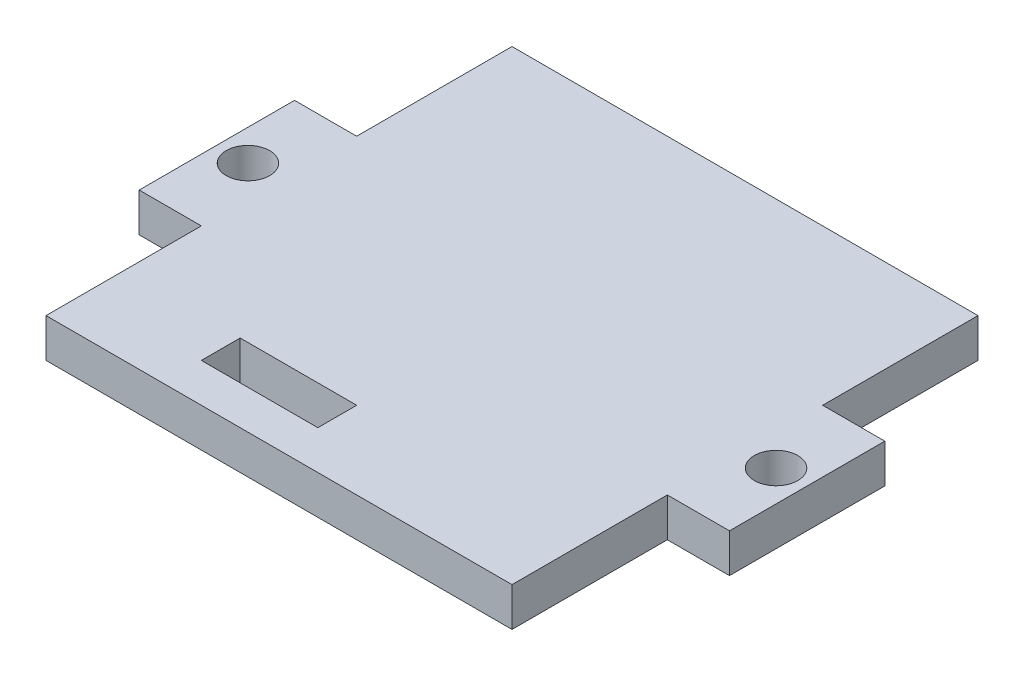
SolidWorks part; units mm, degrees
ref_plane "Front Plane" through (0, 0, 0) normal (0, 0, 1) x (1, 0, 0)
ref_plane "Top Plane" through (0, 0, 0) normal (0, 1, 0) x (1, 0, 0)
ref_plane "Right Plane" through (0, 0, 0) normal (1, 0, 0) x (0, 0, -1)
sketch "Sketch1" plane through (0, 0, 0) normal (0, 1, 0) x (1, 0, 0)
  line L0 (0, 0) -> (0, 12.7)
  line L1 (0, 38.1) -> (38.1, 38.1)
  line L2 (38.1, 38.1) -> (38.1, 25.4)
  line L3 (38.1, 0) -> (0, 0)
  line L4 (0, 25.4) -> (-5.08, 25.4)
  line L6 (-5.08, 25.4) -> (-5.08, 12.7)
  line L7 (-5.08, 12.7) -> (0, 12.7)
  line L8 (38.1, 12.7) -> (43.18, 12.7)
  line L9 (43.18, 12.7) -> (43.18, 25.4)
  line L11 (43.18, 25.4) -> (38.1, 25.4)
  line L13 (0, 19.05) -> (38.1, 19.05) construction
  line L15 (0, 25.4) -> (0, 38.1)
  line L16 (38.1, 12.7) -> (38.1, 0)
  line L18 (9.525, 6.35) -> (19.05, 6.35)
  line L19 (9.525, 6.35) -> (9.525, 3.175)
  line L20 (9.525, 3.175) -> (19.05, 3.175)
  line L21 (19.05, 6.35) -> (19.05, 3.175)
  circle A0 centre (-2.54, 19.05) radius 1.778
  circle A1 centre (40.64, 19.05) radius 1.778
  dimension "D3" = 5.08
  dimension "D7" = 3.556
  dimension "D16" = 6.35
  dimension "D5" = 3.556
  dimension "D1" = 38.1
  dimension "D2" = 38.1
  dimension "D4" = 19.05
  dimension "D6" = 5.08
  dimension "D8" = 6.35
  dimension "D9" = 6.35
  dimension "D10" = 9.525
  dimension "D11" = 3.175
  dimension "D12" = 3.175
  dimension "D13" = 9.525
  dimension "D14" = 2.54
  dimension "D15" = 2.54
  dimension "D17" = 6.35
extrude "Boss-Extrude1" add sketch "Sketch1" along normal blind 3.175
equation "\"Plywood Thickness\"= 0.125in"
equation "\"D1@Boss-Extrude1\"=\"Plywood Thickness\""
equation "\"D11@Sketch1\"=\"Plywood Thickness\""
equation "\"D12@Sketch1\"=\"Plywood Thickness\""
